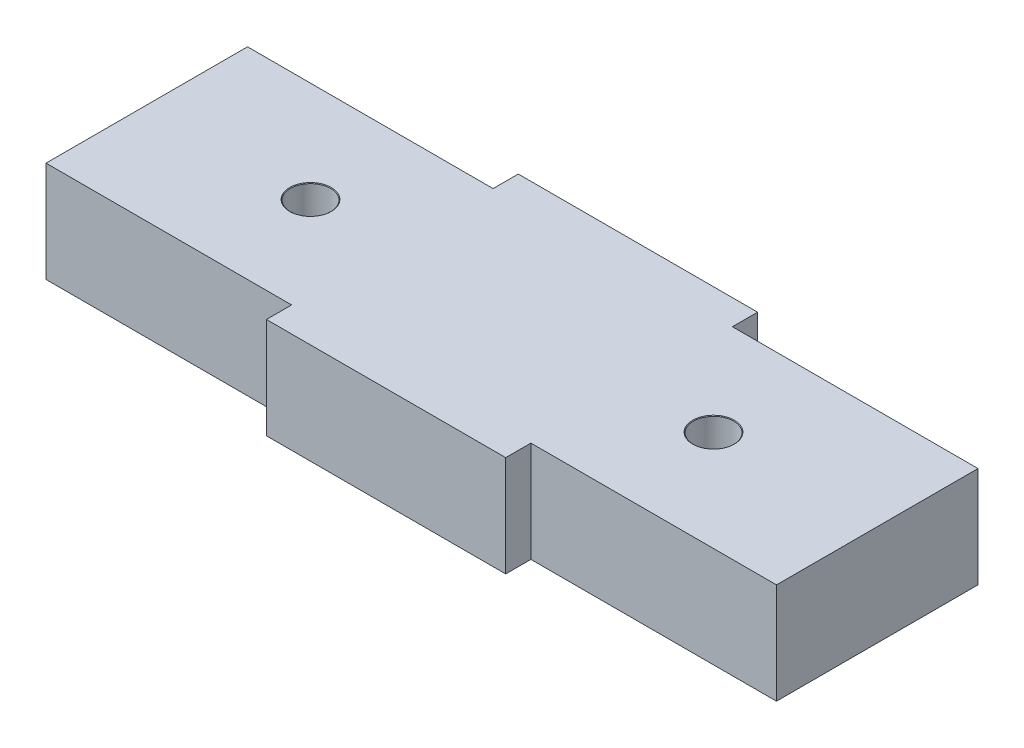
SolidWorks part; units mm, degrees
ref_plane "Front Plane" through (0, 0, 0) normal (0, 0, 1) x (1, 0, 0)
ref_plane "Top Plane" through (0, 0, 0) normal (0, 1, 0) x (1, 0, 0)
ref_plane "Right Plane" through (0, 0, 0) normal (1, 0, 0) x (0, 0, -1)
sketch "Sketch1" plane through (0, 0, 0) normal (0, 1, 0) x (1, 0, 0)
  line L1 (0, 0) -> (29, 0)
  line L2 (0, 0) -> (0, 8)
  line L3 (0, 8) -> (29, 8)
  line L4 (29, 0) -> (29, 8)
  point P5 (0, 0)
  point P6 (0, 0)
extrude "Boss-Extrude1" add sketch "Sketch1" along normal blind 4
sketch "Sketch2" plane through (0, 0, 0) normal (0, 0, 1) x (1, 0, 0)
  line L0 (0, 0) -> (29, 0) construction
  line L1 (9.75, 0) -> (19.25, 0)
  line L2 (9.75, 0) -> (9.75, 4)
  line L3 (9.75, 4) -> (19.25, 4)
  line L4 (19.25, 0) -> (19.25, 4)
  line L5 (0, 4) -> (29, 4) construction
  point P8 (0, 0)
  point P9 (0, 0)
  point P10 (0, 0)
  point P11 (0, 0)
  point P12 (0, 0)
  point P13 (0, 0)
  point P14 (0, 0)
  point P15 (0, 0)
extrude "Boss-Extrude2" add sketch "Sketch2" along normal blind 1
sketch "Sketch3" plane through (0, 0, -8) normal (0, 0, -1) x (-1, 0, 0)
  line L0 (-29, 0) -> (0, 0) construction
  line L1 (-19.25, 0) -> (-9.75, 0)
  line L2 (-19.25, 0) -> (-19.25, 4)
  line L3 (-19.25, 4) -> (-9.75, 4)
  line L4 (-9.75, 0) -> (-9.75, 4)
  line L5 (-29, 4) -> (0, 4) construction
  point P8 (0, 0)
  point P9 (0, 0)
  point P10 (0, 0)
  point P11 (0, 0)
extrude "Boss-Extrude3" add sketch "Sketch3" along normal blind 1
sketch "Sketch4" plane through (0, 4, 0) normal (0, 1, 0) x (1, 0, 0)
  circle A1 centre (6.5, 4) radius 2
  circle A2 centre (22.5, 4) radius 2
hole_wizard "Tap Drill for M2 Tap1" positions "Sketch9" profile "Sketch11" hole size "M2" standard "AS" end condition through all
sketch "Sketch9" plane through (0, 4, 0) normal (0, 1, 0) x (1, 0, 0)
  point P0 (6.5, 4)
  point P3 (22.5, 4)
sketch "Sketch11" plane through (6.5, 4, -4) normal (1, 0, 0) x (0, 0, 1)
  line L0 (0, 0) -> (0, 4)
  line L1 (0, 4) -> (0.8, 4)
  line L2 (0.8, 4) -> (0.8, 0.021)
  line L3 (0.8, 0.021) -> (0.825, 0)
  line L5 (0.825, 0) -> (0, 0)
  line L6 (-0.8, 0.021) -> (-0.825, 0) construction
  line L11 (0, -6.35) -> (0, 107.95) construction
  dimension "Thru Hole Dia." = 1.6
  dimension "Thru Hole Depth" = 4
  dimension "Near C'Sink Dia." = 1.65
  dimension "Near C'Sink Angle" = 100
